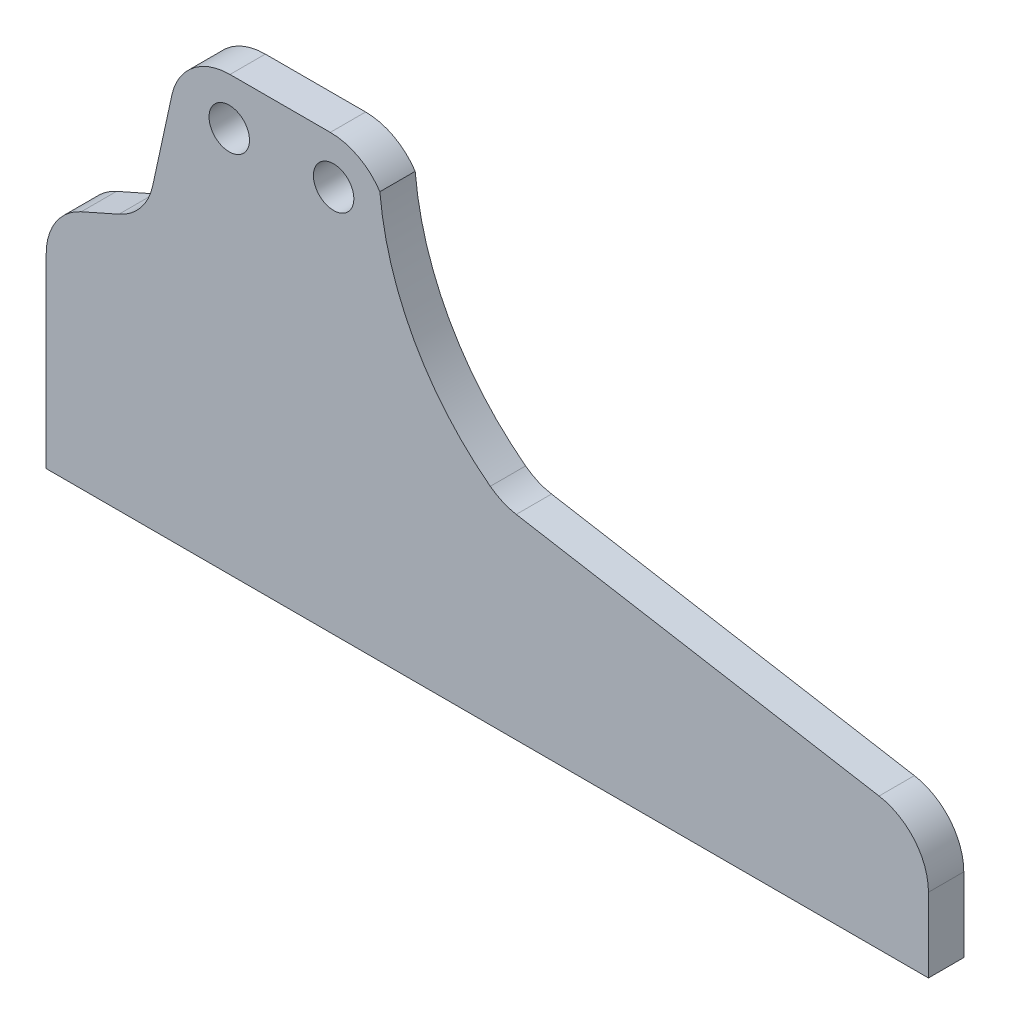
SolidWorks part; units mm, degrees
ref_plane "Alzado" through (0, 0, 0) normal (0, 0, 1) x (1, 0, 0)
ref_plane "Planta" through (0, 0, 0) normal (0, 1, 0) x (1, 0, 0)
ref_plane "Vista lateral" through (0, 0, 0) normal (1, 0, 0) x (0, 0, -1)
sketch "Croquis2" plane through (0, 0, 0) normal (0, 0, 1) x (1, 0, 0)
  line L0 (75.4762, -42.3627) -> (-74.411, -42.3627)
  line L1 (-74.411, -42.3627) -> (-74.411, -10.731)
  line L2 (-68.4602, -1.5875) -> (-62.0496, 1.2515)
  line L3 (-56.3271, 8.2707) -> (-53.0633, 23.2844)
  line L4 (-43.1863, 31.2448) -> (-26.1484, 31.2448)
  line L5 (5.4435, -9.1689) -> (67.0838, -19.7827)
  line L8 (75.4762, -29.7438) -> (75.4762, -42.3627)
  circle A0 centre (-25.5822, 23.4711) radius 3.4355
  circle A1 centre (-43.3161, 23.2282) radius 3.4355
  arc A2 (-74.411, -10.731) -> (-68.4602, -1.5875) centre (-64.411, -10.731) cw
  arc A3 (-62.0496, 1.2515) -> (-56.3271, 8.2707) centre (-66.0989, 10.395) ccw
  arc A4 (-53.0633, 23.2844) -> (-43.1863, 31.2448) centre (-43.1863, 21.1372) cw
  arc A5 (-26.1484, 31.2448) -> (-17.7252, 26.7241) centre (-26.1484, 21.1372) cw
  arc A6 (-17.7252, 26.7241) -> (1.0295, -7.2451) centre (30.2213, 31.0339) ccw
  arc A7 (67.0838, -19.7827) -> (75.4762, -29.7438) centre (65.3686, -29.7438) cw
  arc A8 (1.0295, -7.2451) -> (5.4435, -9.1689) centre (7.1587, 0.7921) ccw
  dimension "D1" = 10
  dimension "D2" = 10
  dimension "D3" = 10.1076
  dimension "D4" = 10.1076
  dimension "D5" = 10.1076
  dimension "D6" = 10.1076
extrude "Saliente-Extruir1" add sketch "Croquis2" along normal blind 6
